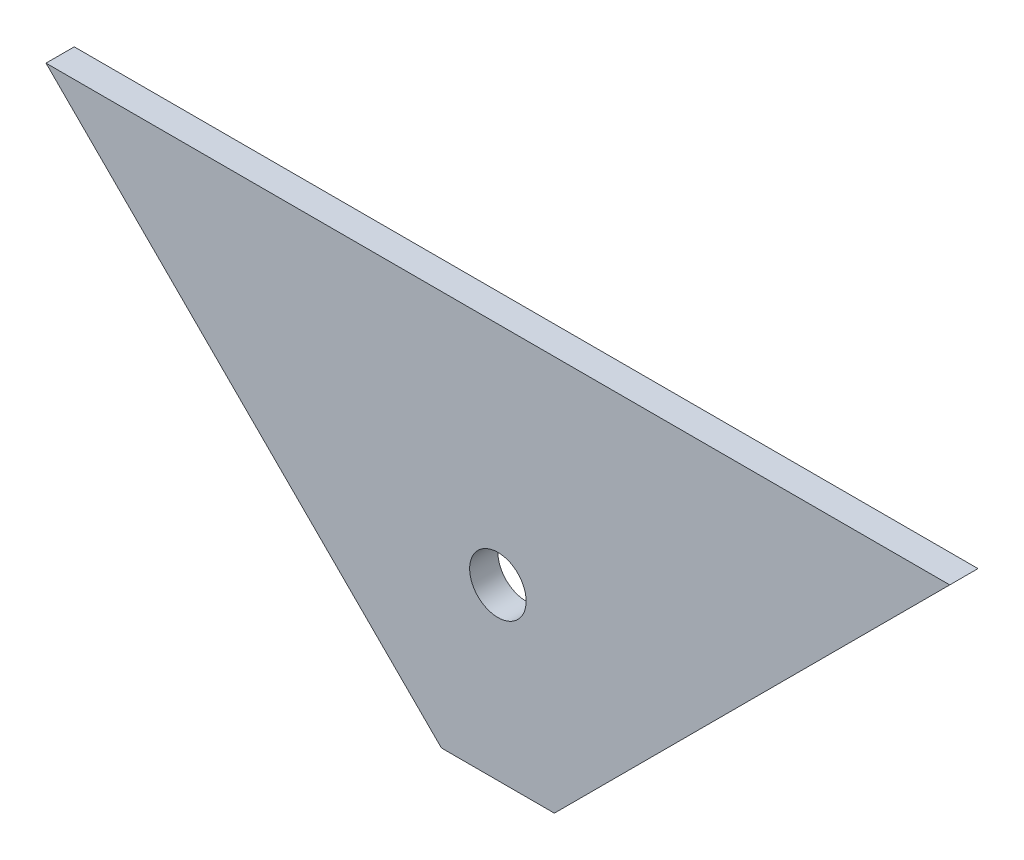
SolidWorks part; units mm, degrees
material "Cedar"
ref_plane "Front Plane" through (0, 0, 0) normal (0, 0, 1) x (1, 0, 0)
ref_plane "Top Plane" through (0, 0, 0) normal (0, 1, 0) x (1, 0, 0)
ref_plane "Right Plane" through (0, 0, 0) normal (1, 0, 0) x (0, 0, -1)
sketch "Sketch1" plane through (0, 0, 0) normal (0, 0, 1) x (1, 0, 0)
  line L0 (-101.6, 0) -> (-12.7, -88.9)
  line L1 (12.7, -88.9) -> (101.6, 0)
  line L2 (101.6, 0) -> (-101.6, 0)
  line L3 (-12.7, -88.9) -> (12.7, -88.9)
  dimension "D1" = 45
  dimension "D2" = 88.9
  dimension "D3" = 25.4
  dimension "D4" = 45
  dimension "D5" = 12.7
extrude "Boss-Extrude1" add sketch "Sketch1" along normal mid plane 6.35
sketch "Sketch2" plane through (0, 0, 3.175) normal (0, 0, 1) x (1, 0, 0)
  circle A0 centre (0, -50.8) radius 6.35
  point P2 (0, 0)
  dimension "D1" = 12.7
  dimension "D2" = 50.8
  dimension "D3" = 101.6
extrude "Cut-Extrude1" cut sketch "Sketch2" against normal through all
